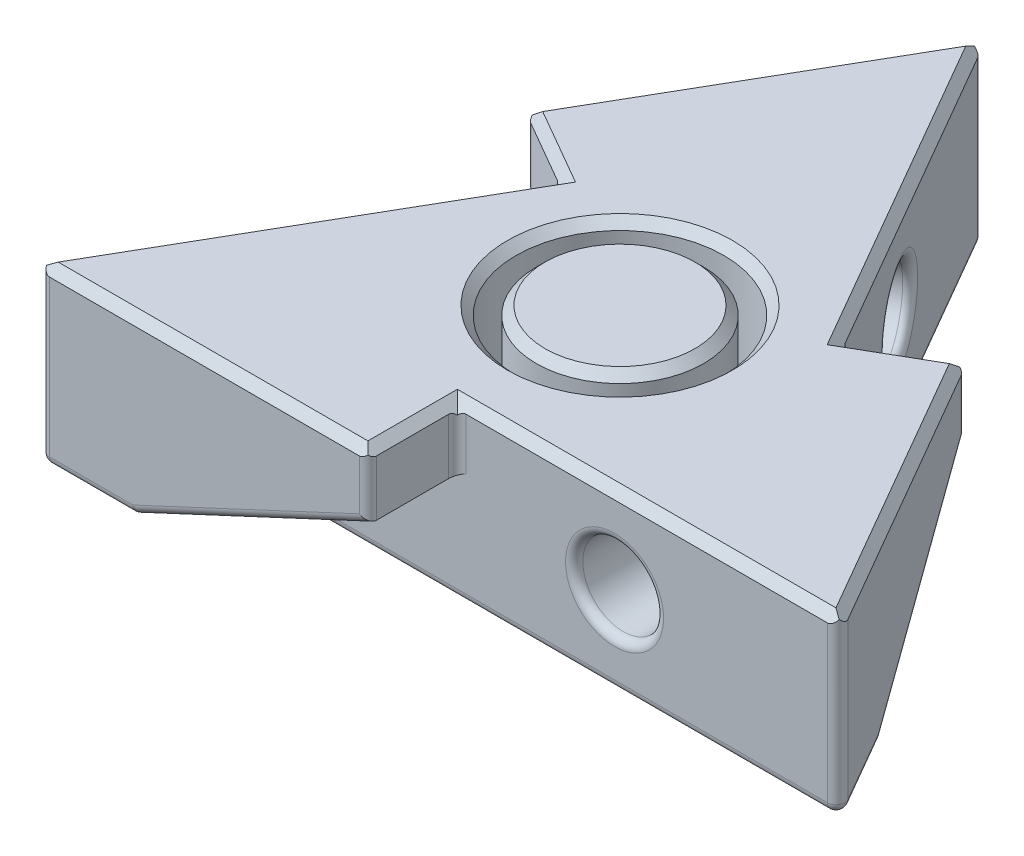
SolidWorks part; units mm, degrees
material "6061-T6 (SS)"
ref_plane "Front Plane" through (0, 0, 0) normal (0, 0, 1) x (1, 0, 0)
ref_plane "Top Plane" through (0, 0, 0) normal (0, 1, 0) x (1, 0, 0)
ref_plane "Right Plane" through (0, 0, 0) normal (1, 0, 0) x (0, 0, -1)
sketch "Sketch1" plane through (0, 0, 0) normal (0, 1, 0) x (1, 0, 0)
  line L3 (-23.1108, -17.4764) -> (-9.7656, 5.6382)
  line L4 (-9.7656, 5.6382) -> (-15.135, 8.7382)
  line L5 (-15.135, 8.7382) -> (-3.5796, 28.7527)
  line L6 (-3.5796, 28.7527) -> (9.7656, 5.6382)
  line L7 (9.7656, 5.6382) -> (15.135, 8.7382)
  line L8 (15.135, 8.7382) -> (26.6904, -11.2764)
  line L9 (26.6904, -11.2764) -> (0, -11.2764)
  line L10 (0, -11.2764) -> (0, -17.4764)
  line L11 (0, -17.4764) -> (-23.1108, -17.4764)
  line L12 (0, 0) -> (0, -11.2764) construction
  line L13 (0, 0) -> (-9.7656, 5.6382) construction
  line L14 (0, 0) -> (9.7656, 5.6382) construction
  line L15 (-15.2156, -3.8015) -> (-6.4688, -8.8515) construction
  line L16 (-6.4688, -8.8515) -> (-5.0688, -6.4266) construction
  line L17 (-5.0688, -6.4266) -> (-13.8156, -1.3766) construction
  line L18 (-5.0688, -6.4266) -> (-7.8688, -11.2764) construction
  circle A0 centre (0, 0) radius 7.2
  point P16 (-6.4688, -8.8515)
  dimension "D1" = 14.4
  dimension "D2" = 6.2
  dimension "D3" = 10.1
  dimension "D4" = 120
  dimension "D5" = 120
  dimension "D6" = 8.1
  dimension "D7" = 2.8
extrude "Boss-Extrude1" add sketch "Sketch1" along normal blind 12
sketch "Sketch2" plane through (0, 0, 0) normal (0, -1, 0) x (1, 0, 0)
  circle A0 centre (0, 0) radius 7.2
  circle A1 centre (0, 0) radius 7.2 construction
extrude "Boss-Extrude2" add sketch "Sketch2" against normal blind 2
sketch "Sketch3" plane through (0, 0, 11.2764) normal (0, 0, 1) x (1, 0, 0)
  line L0 (0, 12) -> (0, 0) construction
  line L2 (26.6904, 12) -> (26.6904, 0) construction
  circle A0 centre (10.9, 6) radius 2.8
  point P0 (10.9, 6)
  point P10 (26.6904, 6)
  dimension "D2" = 5.6
  dimension "D1" = 10.9
extrude "Cut-Extrude1" cut sketch "Sketch3" against normal blind 9.1
sketch "Sketch7" plane through (0, 0, 11.2764) normal (0, 0, 1) x (1, 0, 0)
  line L0 (10.9, 6) -> (-25.9487, -11.1829) construction
  line L1 (13.4357, 0.5622) -> (-23.413, -16.6207)
  line L2 (8.3643, 11.4378) -> (-28.4845, -5.745)
  line L3 (0, 0) -> (26.6904, 0) construction
  arc A0 (13.4357, 0.5622) -> (8.3643, 11.4378) centre (10.9, 6) ccw
  arc A1 (-28.4845, -5.745) -> (-23.413, -16.6207) centre (-25.9487, -11.1829) ccw
  point P3 (-7.5244, -2.5914)
  dimension "D1" = 6
  dimension "D2" = 25
extrude "Cut-Extrude3" cut sketch "Sketch7" along normal through all
sketch "Sketch8" plane through (0, 2, 0) normal (0, 1, 0) x (1, 0, 0)
  circle A0 centre (0, 0) radius 5.8
  dimension "D1" = 11.6
extrude "Boss-Extrude3" add sketch "Sketch8" along normal up to surface (10 mm away) up to face at (0, 12, 0)
pattern_circular "CirPattern2" count 3 over 360 about axis through (0, 0, 0) along (0, 1, 0) of "Cut-Extrude1", "Cut-Extrude3"
chamfer "Chamfer2" distance 0.6 angle 45 11 edges at (0, 12, 7.2) (-16.4382, 12, 5.9191) (-12.4503, 12, -7.1882) (-9.3573, 12, -18.7455) (3.093, 12, -17.1955) (12.4503, 12, -7.1882) (20.9127, 12, 1.2691) (13.3452, 12, 11.2764) (0, 12, 14.3764) (-11.5554, 12, 17.4764) (0, 12, 5.8)
fillet "Fillet3" radius 0.6 24 edges at (7.1341, 0, -10.1961) (-5.3162, 0, -25.7448) (-4.3682, 0, -21.1868) (-12.3972, 0, -1.0802) (-19.6375, 0, 17.4764) (-16.1643, 0, 14.3764) (5.2631, 0, 11.2764) (24.9537, 0, 8.2684) (20.5324, 0, 6.8105) (-23.1108, 5.7, 17.4764) (-8.0821, 3.7688, 17.4764) (0, 9.4688, 17.4764) (0, 9.4688, 11.2764) (26.6904, 5.7, 11.2764) (19.176, 3.7688, -1.7389) (15.135, 9.4688, -8.7382) (9.7656, 9.4688, -5.6382) (-3.5796, 5.7, -28.7527) (-11.0939, 3.7688, -15.7375) (-15.135, 9.4688, -8.7382) (-9.7656, 9.4688, -5.6382) (13.7, 6, 11.2764) (-16.6156, 6, 6.2264) (2.9156, 6, -17.5027)
